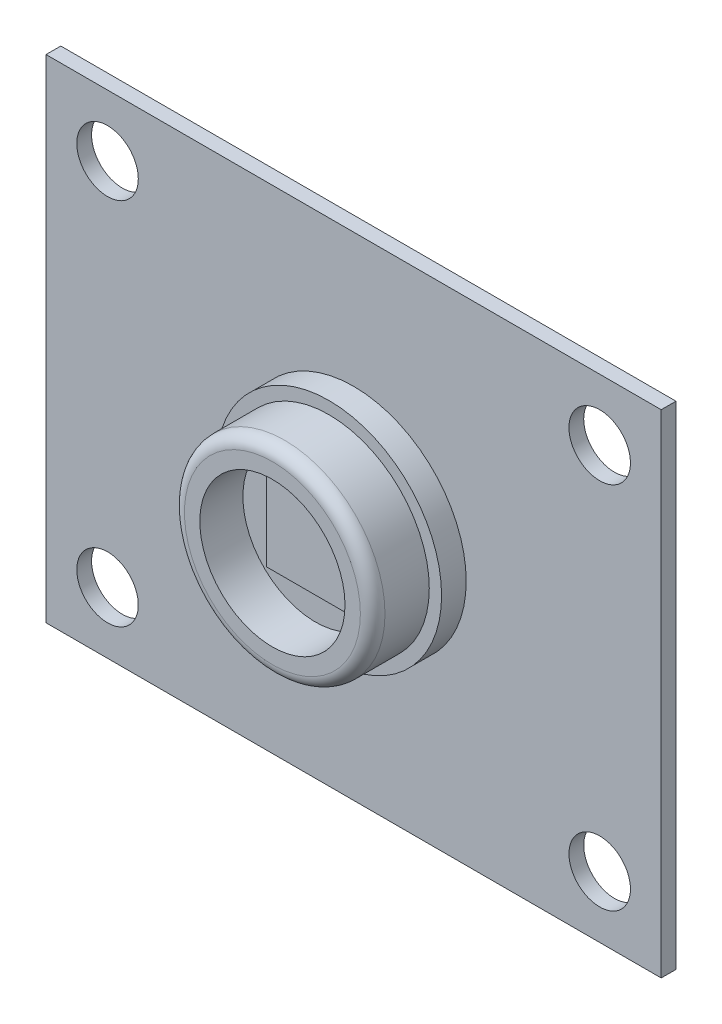
SolidWorks part; units mm, degrees
ref_plane "Front Plane" through (0, 0, 0) normal (0, 0, 1) x (1, 0, 0)
ref_plane "Top Plane" through (0, 0, 0) normal (0, 1, 0) x (1, 0, 0)
ref_plane "Right Plane" through (0, 0, 0) normal (1, 0, 0) x (0, 0, -1)
sketch "Sketch1" plane through (0, 0, 0) normal (0, 0, 1) x (1, 0, 0)
  circle A0 centre (0, 0) radius 4.075
  dimension "D1" = 8.15
extrude "Boss-Extrude1" add sketch "Sketch1" against normal blind 3.3
sketch "Sketch2" plane through (0, 0, -3.3) normal (0, 0, -1) x (-1, 0, 0)
  circle A0 centre (0, 0) radius 4.575
  dimension "D1" = 9.15
extrude "Boss-Extrude2" add sketch "Sketch2" against normal blind 1
sketch "Sketch3" plane through (0, 0, 0) normal (0, 0, 1) x (1, 0, 0)
  circle A0 centre (0, 0) radius 2.95
  dimension "D1" = 5.9
extrude "Cut-Extrude1" cut sketch "Sketch3" against normal blind 1.75
fillet "Fillet1" radius 0.5 1 edges at (4.075, 0, 0)
sketch "Sketch5" plane through (0, 0, -3.3) normal (0, 0, -1) x (-1, 0, 0)
  line L0 (0, 0) -> (-2.5, 0) construction
  line L1 (0, 0) -> (2.5, 0) construction
  circle A0 centre (2.5, 0) radius 0.225
  circle A1 centre (-2.5, 0) radius 0.225
  dimension "D3" = 0.45
  dimension "D4" = 0.45
  dimension "D1" = 2.5
  dimension "D2" = 2.5
extrude "Boss-Extrude4" add sketch "Sketch5" along normal blind 1
sketch "Sketch6" plane through (0, 0, -3.3) normal (0, 0, -1) x (-1, 0, 0)
  line L0 (12.5, 0) -> (-12.5, 0) construction
  line L1 (12.5, 10) -> (-12.5, 10)
  line L2 (12.5, 10) -> (12.5, -10)
  line L3 (12.5, -10) -> (-12.5, -10)
  line L4 (-12.5, 10) -> (-12.5, -10)
  line L5 (12.5, 10) -> (-12.5, -10) construction
  line L6 (12.5, -10) -> (-12.5, 10) construction
  line L7 (0, -10) -> (0, 10) construction
  circle A0 centre (10, -7.5) radius 1.25
  circle A1 centre (10, 7.5) radius 1.25
  circle A2 centre (-10, 7.5) radius 1.25
  circle A3 centre (-10, -7.5) radius 1.25
  point P0 (0, 0)
  dimension "D3" = 2.5
  dimension "D4" = 2.5
  dimension "D5" = 2.5
  dimension "D1" = 25
  dimension "D2" = 20
extrude "Boss-Extrude5" add sketch "Sketch6" along normal blind 0.6
sketch "Sketch7" plane through (0, 0, -3.3) normal (0, 0, 1) x (1, 0, 0)
  line L1 (-1.9, -1.9) -> (1.9, -1.9)
  line L2 (-1.9, -1.9) -> (-1.9, 1.9)
  line L3 (-1.9, 1.9) -> (1.9, 1.9)
  line L4 (1.9, -1.9) -> (1.9, 1.9)
  line L5 (-1.9, -1.9) -> (1.9, 1.9) construction
  line L6 (-1.9, 1.9) -> (1.9, -1.9) construction
  point P0 (0, 0)
  dimension "D1" = 3.8
  dimension "D2" = 3.8
extrude "Active_area" add sketch "Sketch7" along normal blind 0.1 from offset 1.55 separate body
